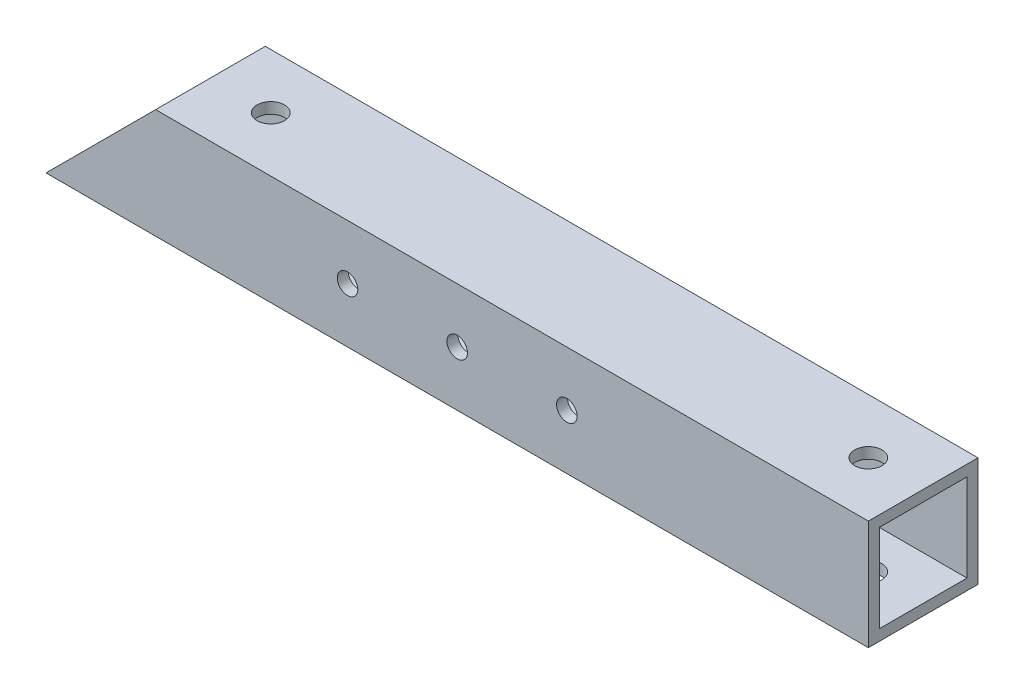
SolidWorks part; units mm, degrees
ref_plane "Front Plane" through (0, 0, 0) normal (0, 0, 1) x (1, 0, 0)
ref_plane "Top Plane" through (0, 0, 0) normal (0, 1, 0) x (1, 0, 0)
ref_plane "Right Plane" through (0, 0, 0) normal (1, 0, 0) x (0, 0, -1)
sketch "Sketch1" plane through (0, 0, 0) normal (1, 0, 0) x (0, 0, -1)
  line L0 (-10.16, 10.16) -> (10.16, 10.16)
  line L1 (-12.7, -12.7) -> (12.7, -12.7)
  line L2 (-12.7, -12.7) -> (-12.7, 12.7)
  line L3 (-12.7, 12.7) -> (12.7, 12.7)
  line L4 (12.7, -12.7) -> (12.7, 12.7)
  line L5 (-12.7, -12.7) -> (12.7, 12.7) construction
  line L6 (-12.7, 12.7) -> (12.7, -12.7) construction
  line L7 (10.16, -10.16) -> (10.16, 10.16)
  line L8 (-10.16, -10.16) -> (10.16, -10.16)
  line L9 (-10.16, -10.16) -> (-10.16, 10.16)
  point P0 (0, 0)
  dimension "D1" = 25.4
  dimension "D2" = 25.4
  dimension "D3" = 2.54
extrude "Boss-Extrude1" add sketch "Sketch1" along normal blind 190.5
sketch "Sketch2" plane through (0, 0, 12.7) normal (0, 0, 1) x (1, 0, 0)
  line L0 (0, -12.7) -> (25.4, 12.7)
  line L1 (190.5, 12.7) -> (0, 12.7) construction
  line L2 (25.4, 12.7) -> (0, 12.7)
  line L3 (0, 12.7) -> (0, -12.7)
  dimension "D1" = 25.4
extrude "Cut-Extrude1" cut sketch "Sketch2" against normal through all
sketch "Sketch3" plane through (0, 12.7, 0) normal (0, 1, 0) x (1, 0, 0)
  line L0 (190.5, 0) -> (25.4, 0) construction
  line L1 (190.5, 12.7) -> (190.5, -12.7) construction
  line L2 (25.4, 12.7) -> (25.4, -12.7) construction
  circle A0 centre (177.8, 0) radius 3.175
  circle A1 centre (39.37, 0) radius 3.175
  dimension "D1" = 6.35
  dimension "D2" = 12.7
  dimension "D3" = 2
extrude "Cut-Extrude2" cut sketch "Sketch3" against normal through all
sketch "Sketch4" plane through (0, 0, 12.7) normal (0, 0, 1) x (1, 0, 0)
  line L0 (190.5, 0) -> (0, 0) construction
  line L1 (190.5, 12.7) -> (190.5, -12.7) construction
  circle A0 centre (95.25, 0) radius 2.3813
  circle A1 centre (120.65, 0) radius 2.3813
  circle A2 centre (69.85, 0) radius 2.3813
  dimension "D1" = 4.7625
  dimension "D2" = 2
  dimension "D3" = 2
extrude "Cut-Extrude3" cut sketch "Sketch4" against normal through all
